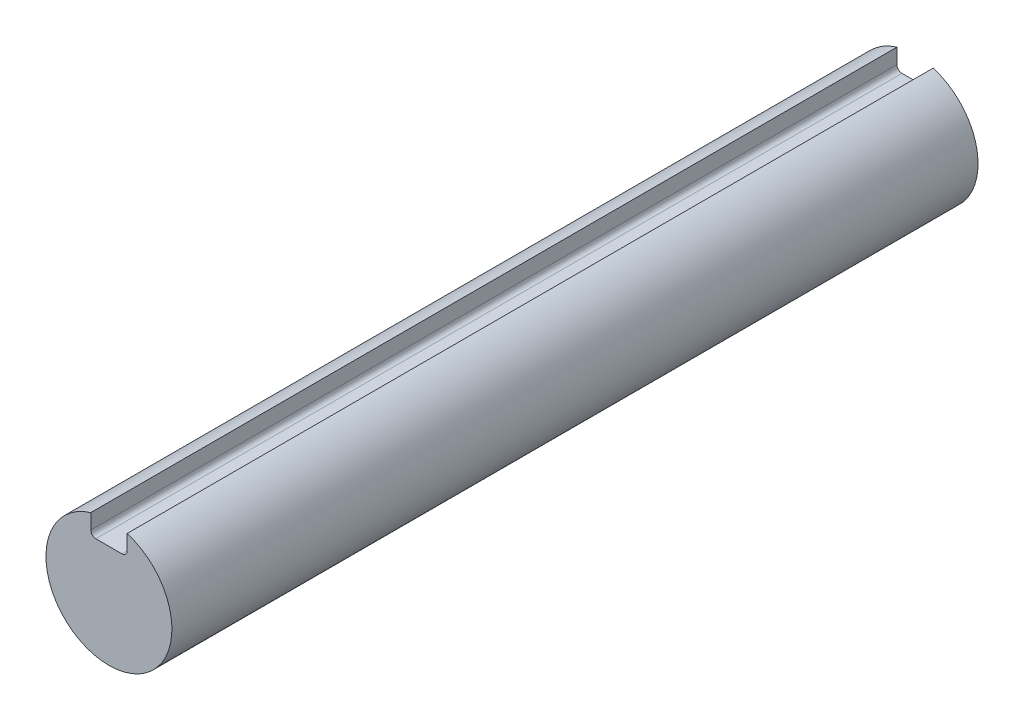
SolidWorks part; units mm, degrees
material "Chrome Stainless Steel"
ref_plane "Front Plane" through (0, 0, 0) normal (0, 0, 1) x (1, 0, 0)
ref_plane "Top Plane" through (0, 0, 0) normal (0, 1, 0) x (1, 0, 0)
ref_plane "Right Plane" through (0, 0, 0) normal (1, 0, 0) x (0, 0, -1)
ref_plane "Plane1" through (0, 0, -302.26) normal (0, 0, -1) x (-1, 0, 0)
sketch "Sketch1" plane through (0, 0, -302.26) normal (0, 0, -1) x (-1, 0, 0)
  line L0 (2.286, 7.6012) -> (2.286, 5.6962)
  line L1 (1.651, 5.0612) -> (-1.651, 5.0612)
  line L2 (-2.286, 5.6962) -> (-2.286, 7.6012)
  arc A0 (-2.286, 7.6012) -> (2.286, 7.6012) centre (0, 0) ccw
  arc A1 (2.286, 5.6962) -> (1.651, 5.0612) centre (1.651, 5.6962) cw
  arc A2 (-1.651, 5.0612) -> (-2.286, 5.6962) centre (-1.651, 5.6962) cw
extrude "Boss-Extrude1" add sketch "Sketch1" against normal blind 101.6
